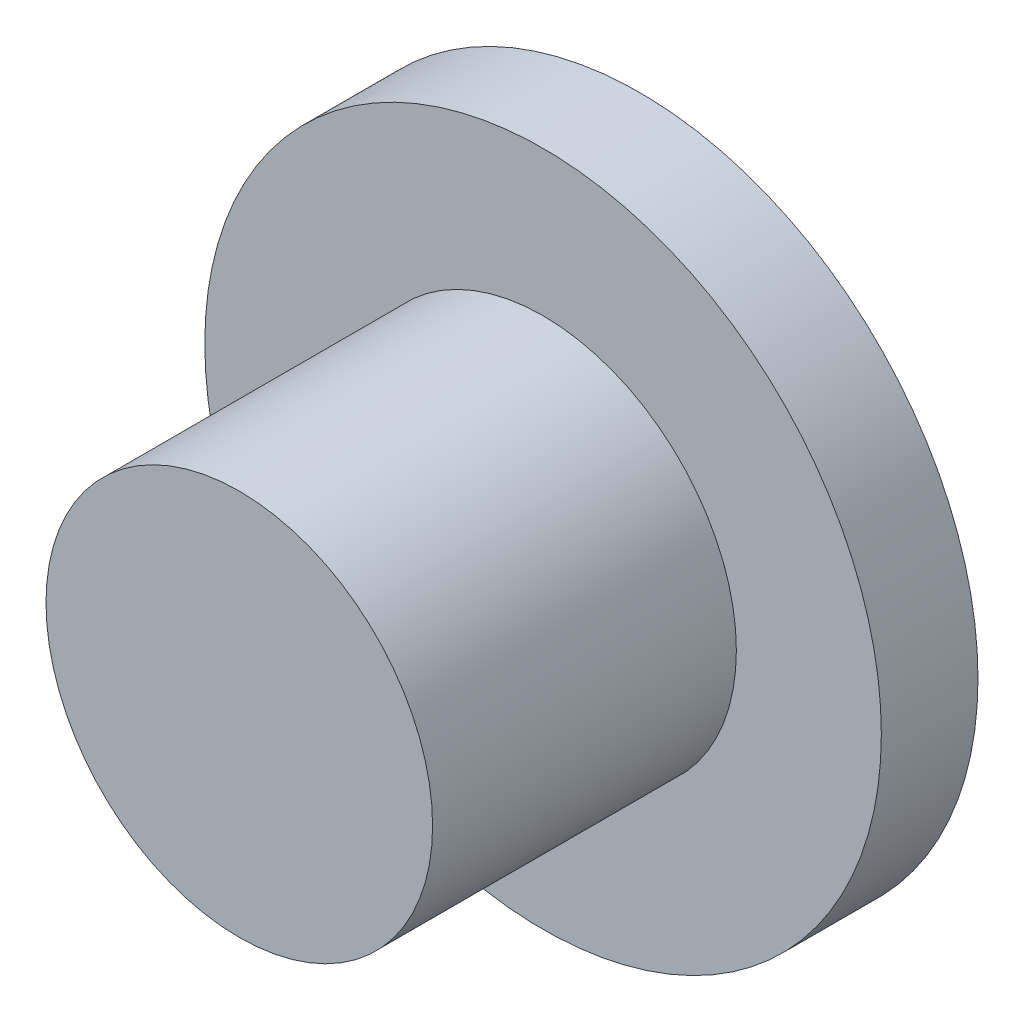
SolidWorks part; units mm, degrees
ref_plane "Front Plane" through (0, 0, 0) normal (0, 0, 1) x (1, 0, 0)
ref_plane "Top Plane" through (0, 0, 0) normal (0, 1, 0) x (1, 0, 0)
ref_plane "Right Plane" through (0, 0, 0) normal (1, 0, 0) x (0, 0, -1)
sketch "Sketch1" plane through (0, 0, 0) normal (0, 0, 1) x (1, 0, 0)
  circle A0 centre (0, 0) radius 2.45
  dimension "D1" = 4.9
extrude "Boss-Extrude1" add sketch "Sketch1" along normal blind 0.7
sketch "Sketch2" plane through (0, 0, 0) normal (0, 0, 1) x (1, 0, 0)
  circle A0 centre (0, 0) radius 1.4
  dimension "D1" = 2.8
extrude "Boss-Extrude2" add sketch "Sketch2" along normal blind 2.9
